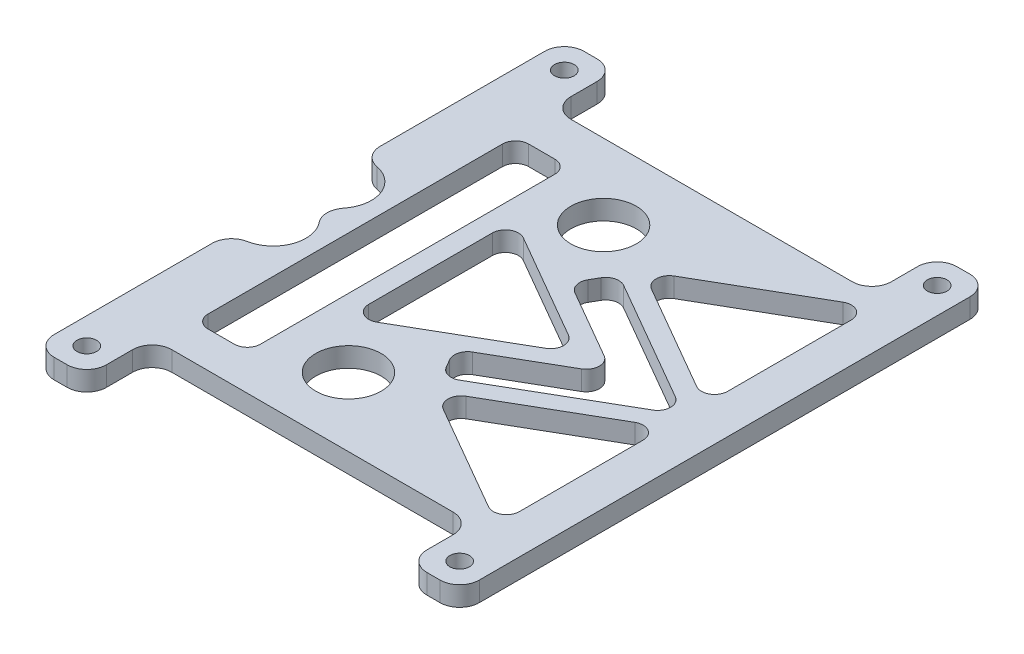
SolidWorks part; units mm, degrees
material "ABS"
ref_plane "Спереди" through (0, 0, 0) normal (0, 0, 1) x (1, 0, 0)
ref_plane "Сверху" through (0, 0, 0) normal (0, 1, 0) x (1, 0, 0)
ref_plane "Справа" through (0, 0, 0) normal (1, 0, 0) x (0, 0, -1)
sketch "Sketch1" plane through (0, 0, 0) normal (0, 1, 0) x (1, 0, 0)
  line L0 (10.9056, 0) -> (18.9056, 0) construction
  line L1 (10.9056, 39.7697) -> (10.9056, 61)
  line L2 (18.9056, 0) -> (67.9056, 0)
  line L3 (10.9056, 0) -> (10.9056, 20.2303)
  line L4 (18.9056, 61) -> (67.9056, 61)
  line L5 (75.9056, 0) -> (75.9056, 61)
  line L7 (75.9056, 30.5) -> (18.9056, 30.5) construction
  line L8 (18.9056, 61) -> (18.9056, 71)
  line L9 (10.9056, 0) -> (10.9056, -10)
  line L10 (10.9056, -10) -> (18.9056, -10)
  line L11 (18.9056, 0) -> (18.9056, -10)
  line L12 (14.9056, -6) -> (14.9056, -10) construction
  line L13 (10.9056, 71) -> (18.9056, 71)
  line L14 (10.9056, 61) -> (10.9056, 71)
  line L15 (10.9056, 61) -> (18.9056, 61) construction
  line L17 (75.9056, -2) -> (10.9056, -2) construction
  line L18 (67.9056, 0) -> (75.9056, 0) construction
  line L19 (75.9056, 0) -> (75.9056, -10)
  line L20 (75.9056, -10) -> (67.9056, -10)
  line L21 (67.9056, 0) -> (67.9056, -10)
  line L22 (71.9056, -10) -> (71.9056, -6) construction
  line L23 (14.9056, -6) -> (71.9056, -6) construction
  line L24 (75.9056, 61) -> (75.9056, 71)
  line L25 (75.9056, 71) -> (67.9056, 71)
  line L26 (67.9056, 61) -> (67.9056, 71)
  line L27 (67.9056, 61) -> (75.9056, 61) construction
  circle A0 centre (38.4056, 10.5) radius 5
  circle A1 centre (38.4056, 49.5) radius 5
  arc A2 (12.4056, 30) -> (10.9056, 39.7697) centre (12.4056, 35) ccw
  arc A3 (10.9056, 20.2303) -> (12.4056, 30) centre (12.4056, 25) ccw
  circle A4 centre (14.9056, -6) radius 1.5
  circle A5 centre (14.9056, 67) radius 1.5
  circle A6 centre (71.9056, -6) radius 1.5
  circle A7 centre (71.9056, 67) radius 1.5
  point P0 (0, 0)
  dimension "D1" = 10
  dimension "D2" = 3
  dimension "D3" = 8
  dimension "D4" = 4
  dimension "D5" = 4
extrude "Boss-Extrude1" add sketch "Sketch1" along normal blind 3
fillet "Fillet1" radius 3 15 edges at (75.9056, 1.5, 10) (67.9056, 1.5, 10) (67.9056, 1.5, 0) (18.9056, 1.5, 0) (18.9056, 1.5, 10) (10.9056, 1.5, 10) (10.9056, 1.5, -20.2303) (12.4056, 1.5, -30) (10.9056, 1.5, -39.7697) (10.9056, 1.5, -71) (18.9056, 1.5, -71) (18.9056, 1.5, -61) (67.9056, 1.5, -61) (67.9056, 1.5, -71) (75.9056, 1.5, -71)
sketch "Sketch2" plane through (0, 3, 0) normal (0, 1, 0) x (1, 0, 0)
  line L0 (75.9056, 30.5) -> (38.4056, 30.5) construction
  line L1 (75.9056, -7) -> (75.9056, 68) construction
  line L2 (38.4056, 49.5) -> (38.4056, 10.5) construction
  line L3 (62.4511, 30.5) -> (62.4511, 46.4115) construction
  line L4 (53.3146, 30.5) -> (30.9511, 43.4115)
  line L5 (30.9511, 43.4115) -> (30.9511, 17.5885)
  line L6 (30.9511, 17.5885) -> (53.3146, 30.5)
  line L7 (69.9056, 27.5) -> (69.9056, 1.6769)
  line L8 (47.5422, 46.4115) -> (69.9056, 33.5)
  line L9 (69.9056, 33.5) -> (69.9056, 59.3231)
  line L10 (69.9056, 59.3231) -> (47.5422, 46.4115)
  line L11 (47.5422, 14.5885) -> (69.9056, 27.5)
  line L12 (69.9056, 1.6769) -> (47.5422, 14.5885)
  line L13 (69.655, 30.5) -> (46.1805, 44.053)
  line L14 (58.7614, 30.5) -> (61.4848, 35.2171) construction
  line L15 (46.1805, 44.053) -> (43.4571, 39.3359)
  line L16 (58.7614, 30.5) -> (43.4571, 39.3359)
  line L17 (61.4848, 35.2171) -> (43.4571, 39.3359) construction
  line L18 (46.1805, 44.053) -> (58.7614, 30.5) construction
  line L19 (52.4709, 37.2765) -> (55.1943, 41.9936) construction
  line L20 (52.4709, 37.2765) -> (49.7475, 32.5594) construction
  line L21 (46.1805, 44.053) -> (47.5422, 46.4115) construction
  line L22 (69.655, 30.5) -> (46.1805, 16.947)
  line L23 (46.1805, 16.947) -> (43.4571, 21.6641)
  line L24 (58.7614, 30.5) -> (43.4571, 21.6641)
  line L26 (19.9511, 54.5) -> (27.9511, 54.5)
  line L27 (19.9511, 54.5) -> (19.9511, 5.5)
  line L28 (19.9511, 5.5) -> (27.9511, 5.5)
  line L29 (27.9511, 54.5) -> (27.9511, 5.5)
  line L30 (19.9511, 54.5) -> (27.9511, 5.5) construction
  line L31 (19.9511, 5.5) -> (27.9511, 54.5) construction
  circle A0 centre (38.4056, 30.5) radius 7.4545 construction
  circle A1 centre (38.4056, 49.5) radius 5 construction
  circle A2 centre (62.4511, 46.4115) radius 7.4545 construction
  circle A3 centre (38.4056, 10.5) radius 5 construction
  point P24 (52.4709, 37.2765)
  point P26 (23.9511, 30)
  dimension "D1" = 9
  dimension "D2" = 3
  dimension "D3" = 6
  dimension "D4" = 8
  dimension "D5" = 3
extrude "Cut-Extrude1" cut sketch "Sketch2" against normal through all
fillet "Fillet2" radius 2 19 edges at (69.9056, 1.5, -1.6769) (47.5422, 1.5, -14.5885) (69.9056, 1.5, -27.5) (69.9056, 1.5, -59.3231) (69.9056, 1.5, -33.5) (47.5422, 1.5, -46.4115) (69.655, 1.5, -30.5) (46.1805, 1.5, -44.053) (43.4571, 1.5, -39.3359) (58.7614, 1.5, -30.5) (43.4571, 1.5, -21.6641) (46.1805, 1.5, -16.947) (30.9511, 1.5, -17.5885) (53.3146, 1.5, -30.5) (30.9511, 1.5, -43.4115) (19.9511, 1.5, -5.5) (27.9511, 1.5, -5.5) (27.9511, 1.5, -54.5) (19.9511, 1.5, -54.5)
